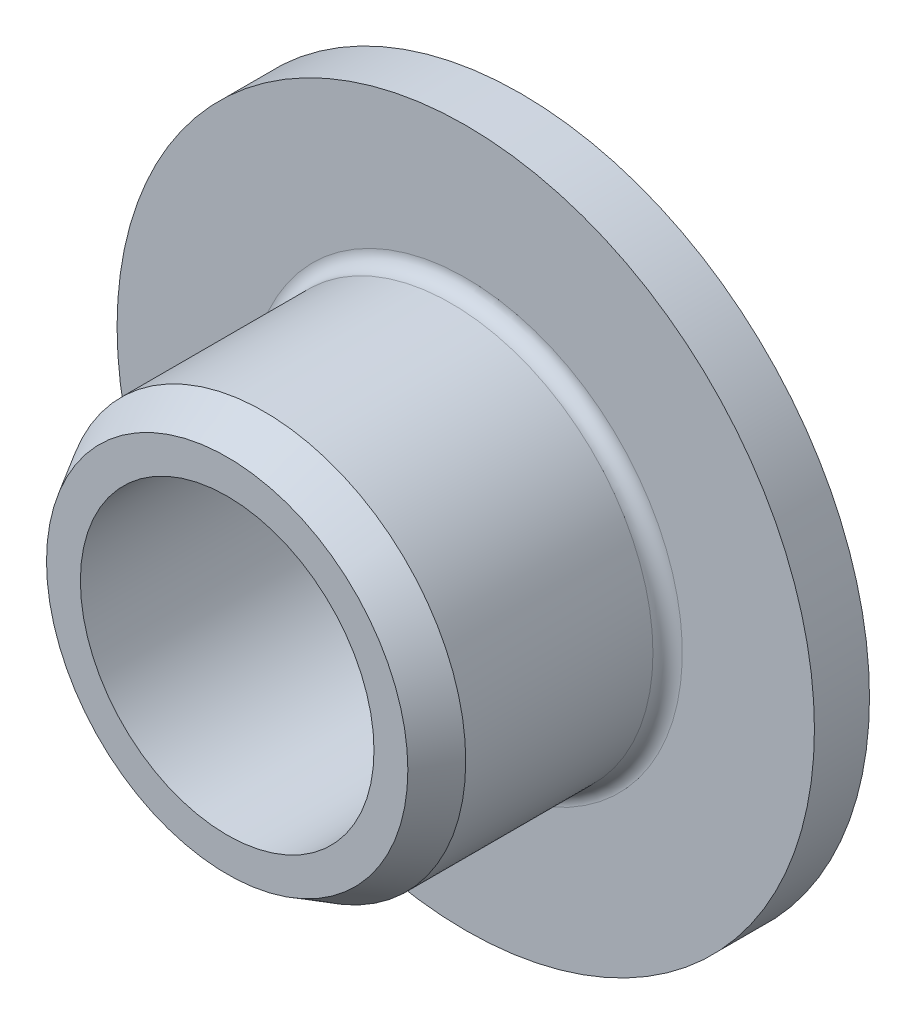
SolidWorks part; units mm, degrees
ref_plane "Přední rovina" through (0, 0, 0) normal (0, 0, 1) x (1, 0, 0)
ref_plane "Vrchní rovina" through (0, 0, 0) normal (0, 1, 0) x (1, 0, 0)
ref_plane "Pravá rovina" through (0, 0, 0) normal (1, 0, 0) x (0, 0, -1)
sketch "Skica1" plane through (0, 0, 0) normal (0, 0, 1) x (1, 0, 0)
  circle A0 centre (0, 0) radius 2
  circle A1 centre (0, 0) radius 2.75
  dimension "d1" = 4
  dimension "d2" = 5.5
extrude "Vysunout1" add sketch "Skica1" along normal blind 4
sketch "Skica2" plane through (0, 0, 0) normal (0, 0, -1) x (-1, 0, 0)
  circle A0 centre (0, 0) radius 4.75
  circle A1 centre (0, 0) radius 2.75 construction
  circle A2 centre (0, 0) radius 2.75
  dimension "d3" = 9.5
extrude "Vysunout2" add sketch "Skica2" against normal blind 0.75
fillet "Zaoblit1" radius 0.2 1 edges at (-2.75, 0, 0.75)
chamfer "Zkosit1" distance 0.5 angle 30 1 edges at (2, 0, 0)
chamfer "Zkosit2" distance 0.5 angle 30 1 edges at (2.75, 0, 4)
equation "\"D1@Zaoblit1\" = \"d1@Skica1\" / 20"
